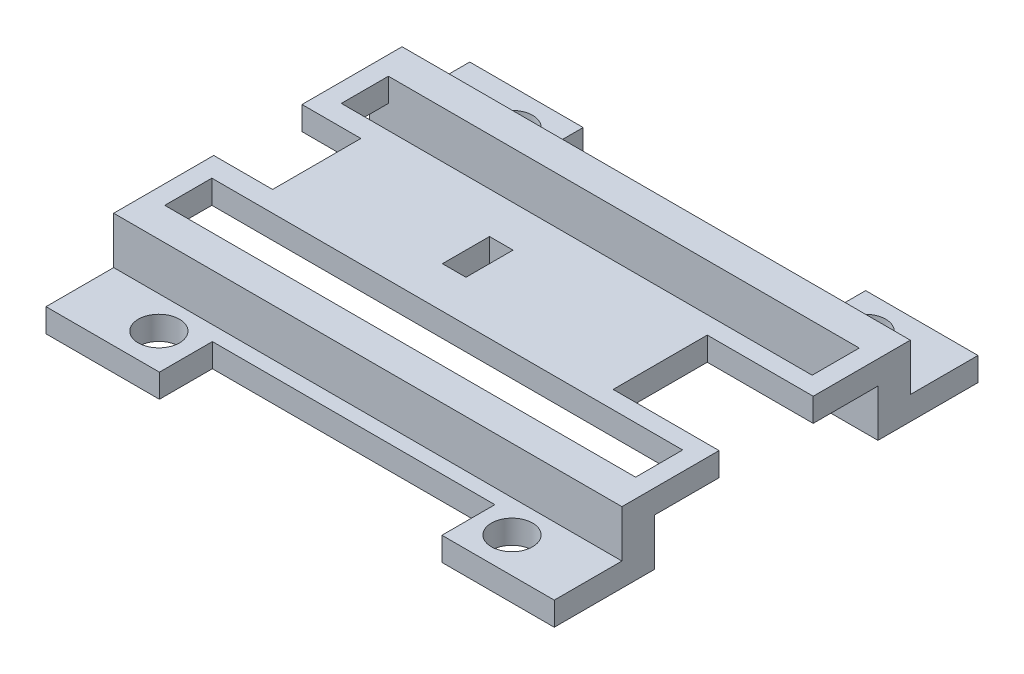
SolidWorks part; units mm, degrees
material "ABS"
ref_plane "Front Plane" through (0, 0, 0) normal (0, 0, 1) x (1, 0, 0)
ref_plane "Top Plane" through (0, 0, 0) normal (0, 1, 0) x (1, 0, 0)
ref_plane "Right Plane" through (0, 0, 0) normal (1, 0, 0) x (0, 0, -1)
sketch "Sketch1" plane through (0, 0, 0) normal (0, 1, 0) x (1, 0, 0)
  line L0 (-34.6173, 0) -> (53.1626, 0) construction
  line L7 (-17.9541, -18) -> (-9.9541, -18)
  line L9 (-17.9541, 18) -> (-9.9541, 18)
  line L20 (19.005, -6.25) -> (19.005, -8.75)
  line L24 (10.0459, 18) -> (10.0459, 12.6161)
  line L26 (19.005, -8.75) -> (18.5047, -8.75)
  line L31 (10.0459, 12.6161) -> (-9.9541, 12.6161)
  line L32 (-9.9541, 18) -> (-9.9541, 12.6161)
  line L33 (-21.59, -18) -> (-9.9541, -18)
  line L34 (-21.59, -18) -> (-21.59, 18)
  line L35 (-21.59, 18) -> (-9.9541, 18)
  line L36 (21.59, -18) -> (21.59, 18)
  line L37 (0, 0) -> (0, 6.25)
  line L38 (18.5047, -6.25) -> (19.005, -6.25)
  line L39 (10.0459, -12.6161) -> (-9.9541, -12.6161)
  line L40 (-9.9541, -18) -> (-9.9541, -12.6161)
  line L42 (10.0459, -18) -> (10.0459, -12.6161)
  line L43 (10.0459, -18) -> (21.59, -18)
  line L44 (10.0459, -18) -> (18.0459, -18)
  line L45 (10.0459, 18) -> (18.0459, 18)
  line L46 (10.0459, 18) -> (21.59, 18)
  line L47 (18.5047, -6.25) -> (-18.5, -6.25)
  line L48 (-19.0045, -6.25) -> (-18.5, -6.25)
  line L49 (-19.0045, -8.75) -> (-19.0045, -6.25)
  line L50 (-18.5, 8.75) -> (18.5047, 8.75)
  line L51 (18.5047, 6.25) -> (-18.5, 6.25)
  line L52 (-18.5, -8.75) -> (-19.0045, -8.75)
  line L53 (0.0024, 8.75) -> (-18.5, 8.75)
  line L54 (0.0024, 8.75) -> (18.5047, 8.75)
  line L55 (-18.5, 8.75) -> (-19.0045, 8.75)
  line L56 (-19.0045, 8.75) -> (-19.0045, 6.25)
  line L57 (-19.0045, 6.25) -> (-18.5, 6.25)
  line L58 (18.5047, 6.25) -> (19.005, 6.25)
  line L59 (19.005, 6.25) -> (19.005, 8.75)
  line L60 (19.005, 8.75) -> (18.5047, 8.75)
  line L61 (-18.5, -8.75) -> (18.5047, -8.75)
  circle A0 centre (-15, 15) radius 1.75
  circle A1 centre (15, 15) radius 1.75
  circle A2 centre (15, -15) radius 1.75
  circle A3 centre (-15, -15) radius 1.75
  point P0 (0, 0)
  point P10 (0, 0)
  point P15 (0, 0)
  point P16 (0, 0)
  point P17 (0.0459, 18)
  point P24 (0, 0)
  dimension "D3" = 3.5
  dimension "D4" = 3.5
  dimension "D5" = 3.5
  dimension "D6" = 3.5
  dimension "D11" = 2.5
  dimension "D12" = 38.0095
  dimension "D13" = 18.5024
  dimension "D14" = 38.0095
  dimension "D1" = 30
  dimension "D2" = 30
  dimension "D7" = 36
  dimension "D8" = 36
  dimension "D9" = 43.18
  dimension "D10" = 20
extrude "Boss-Extrude3" add sketch "Sketch1" along normal blind 3
sketch "Sketch3" plane through (0, 3, 0) normal (0, 1, 0) x (1, 0, 0)
  line L0 (0, 0) -> (-16.59, 0)
  line L1 (-21.59, 9.27) -> (21.59, 9.27)
  line L2 (-21.59, 9.27) -> (-21.59, -9.27)
  line L3 (-21.59, -9.27) -> (21.59, -9.27)
  line L4 (21.59, 9.27) -> (21.59, -9.27)
  line L5 (-21.59, 9.27) -> (21.59, -9.27) construction
  line L6 (-21.59, -9.27) -> (21.59, 9.27) construction
  line L7 (-16.59, 0) -> (36.4752, 0)
  line L8 (21.59, 0) -> (21.59, 3.9995)
  line L9 (21.59, 3.9995) -> (21.59, -3.9981)
  line L10 (21.59, -3.9981) -> (12.59, -3.9981)
  line L11 (12.59, -3.9981) -> (12.59, 3.9995)
  line L12 (12.59, 3.9995) -> (21.59, 3.9995)
  line L13 (-21.59, 0) -> (-21.59, 3.75)
  line L14 (-21.59, 3.75) -> (-21.59, -3.75)
  line L15 (-21.59, -3.75) -> (-16.59, -3.75)
  line L16 (-16.59, -3.75) -> (-16.59, 3.75)
  line L17 (-16.59, 3.75) -> (-21.59, 3.75)
  line L18 (12.59, 0.0007) -> (-3.408, 0)
  line L19 (-16.59, 0) -> (-4.576, 0)
  line L20 (21.59, 0) -> (-1.9118, 0)
  line L21 (-1.9118, 0) -> (-3.9118, 0)
  line L22 (-3.9118, 0) -> (-3.9118, 2)
  line L23 (-3.9118, 2) -> (-1.9118, 2)
  line L24 (-1.9118, 2) -> (-1.9118, -2)
  line L25 (-1.9118, -2) -> (-3.9118, -2)
  line L26 (-3.9118, -2) -> (-3.9118, -0.0848)
  line L27 (-3.9118, -0.0848) -> (-3.9118, 0)
  line L28 (21.59, -18) -> (21.59, 18) construction
  point P0 (0, 0)
  line M24 (-21.59, 18) -> (-21.59, -18)
  dimension "D1" = 43.18
  dimension "D2" = 18.54
  dimension "D3" = 3.75
  dimension "D4" = 3.75
  dimension "D5" = 5
  dimension "D6" = 23.5018
  dimension "D7" = 2
  dimension "D8" = 2
  dimension "D9" = 2
  dimension "D10" = 12.6782
sketch "Sketch4" plane through (0, 3, 0) normal (0, 1, 0) x (1, 0, 0)
  line L0 (-21.59, -9.27) -> (-21.59, -18)
  line L4 (-21.59, -9.27) -> (-21.59, 9.27)
  line L5 (19.005, -8.9) -> (19.255, -8.9)
  line L6 (21.59, 9.27) -> (19.255, 8.2674) construction
  line L7 (-17.4676, -7.5) -> (-22.2811, -7.5) construction
  line L8 (19.255, 6.1) -> (19.255, 8.8828)
  line L9 (-22.2811, -7.5) -> (-22.2811, 7.5) construction
  line L10 (-22.2811, 7.5) -> (-19.2545, 7.5) construction
  line L11 (-21.59, -18) -> (-9.9541, -18)
  line L12 (-9.9541, -18) -> (-9.9541, -12.6161)
  line L13 (-9.9541, -12.6161) -> (10.0459, -12.6161)
  line L14 (10.0459, -12.6161) -> (10.0459, -18)
  line L15 (10.0459, -18) -> (21.59, -18)
  line L18 (-21.59, 9.27) -> (-21.59, 18)
  line L19 (-21.59, 18) -> (-9.9541, 18)
  line L20 (-9.9541, 18) -> (-9.9541, 12.6161)
  line L21 (-9.9541, 12.6161) -> (10.0459, 12.6161)
  line L22 (10.0459, 12.6161) -> (10.0459, 18)
  line L23 (10.0459, 18) -> (21.59, 18)
  line L26 (19.957, 7.5) -> (19.957, -7.5) construction
  line L27 (19.957, -7.5) -> (19.255, -7.5) construction
  line L28 (19.005, 6.1) -> (19.255, 6.1)
  line L29 (19.005, -8.9) -> (-19.0045, -8.9)
  line L30 (-19.2545, -8.2672) -> (-21.59, -9.27) construction
  line L31 (-25.3402, 0) -> (40.0114, 0) construction
  line L32 (19.255, 7.5) -> (19.957, 7.5) construction
  line L33 (19.005, -6.1) -> (-19.0045, -6.1)
  line L35 (-19.0045, -8.9) -> (19.005, -8.9)
  line L37 (-19.0045, -6.1) -> (19.005, -6.1)
  line L39 (-19.0045, 6.1) -> (19.005, 6.1)
  line L41 (-19.0045, 8.9) -> (19.005, 8.9)
  line L43 (19.255, -8.9) -> (19.255, -6.1)
  line L44 (19.255, -6.1) -> (19.005, -6.1)
  line L45 (-19.0045, -6.1) -> (-19.2545, -6.1)
  line L46 (-19.2545, -6.1) -> (-19.2545, -8.9)
  line L47 (-19.2545, -8.9) -> (-19.0045, -8.9)
  line L48 (19.255, 8.9) -> (19.005, 8.9)
  line L49 (-19.0045, 6.1) -> (-19.2545, 6.1)
  line L50 (14.207, 6.1) -> (-17.4676, -7.5) construction
  line L51 (-19.2545, 8.9) -> (-19.0045, 8.9)
  line L52 (-19.2545, 6.1) -> (-19.2545, 8.9)
  line L54 (19.255, -8.9) -> (-19.2545, -8.9)
  line L55 (19.255, -8.9) -> (19.255, -6.1)
  line L56 (19.255, -6.1) -> (-19.2545, -6.1)
  line L57 (-19.2545, -8.9) -> (-19.2545, -6.1)
  line L58 (-19.2545, 6.1) -> (19.255, 6.1)
  line L59 (-19.2545, 6.1) -> (-19.2545, 8.9)
  line L60 (-19.2545, 8.9) -> (19.255, 8.9)
  line L61 (19.255, 6.1) -> (19.255, 8.9)
  circle A1 centre (15, -15) radius 1.75
  circle A2 centre (-15, -15) radius 1.75
  circle A3 centre (-15, 15) radius 1.75
  circle A4 centre (15, 15) radius 1.7781
  point P0 (0, 0)
  line M27 (19.005, -8.75) -> (-19.0045, -8.75)
  line M28 (-19.0045, -8.75) -> (-19.0045, -6.25)
  line M29 (-19.0045, -6.25) -> (19.005, -6.25)
  line M30 (19.005, -6.25) -> (19.005, -8.75)
  line M31 (19.005, 8.75) -> (19.005, 6.25)
  line M32 (19.005, 6.25) -> (-19.0045, 6.25)
  line M33 (-19.0045, 6.25) -> (-19.0045, 8.75)
  line M34 (-19.0045, 8.75) -> (19.005, 8.75)
  dimension "D1" = 18.54
  dimension "D2" = 43.18
  dimension "D3" = 0.25
  dimension "D4" = 0.25
  dimension "D5" = 38.0095
  dimension "D6" = 0.25
  dimension "D7" = 0.25
sketch "Sketch5" plane through (21.59, 0, 0) normal (1, 0, 0) x (0, 0, -1)
  line L0 (0, -5.6906) -> (0, 9.6238) construction
  line L1 (18, -1) -> (11.53, -1)
  line L2 (-18, 3) -> (-11.53, 3)
  line L3 (-18, 3) -> (-18, -1)
  line L4 (-18, -1) -> (-11.53, -1)
  line L5 (-11.53, 3) -> (-11.53, -1)
  line L6 (11.53, 3) -> (11.53, -1)
  line L7 (18, 3) -> (11.53, 3)
  line L8 (18, 3) -> (18, -1)
  dimension "D1" = 4
  dimension "D2" = 6.47
extrude "Cut-Extrude7" cut sketch "Sketch4" against normal through all contours M31 M34 M33 M32 | L8 L61 L48 L41 L51 L52 L49 L39 L28 M34 M31 M32 M33 | L46 L47 L29 L5 L43 L44 L33 L45 M30 M27 M28 M29
sketch "Sketch7" plane through (21.59, 0, 0) normal (1, 0, 0) x (0, 0, -1)
  line L0 (-18, 0) -> (-18, 1)
  line L5 (-18, 3) -> (-18, -1) construction
  line L7 (18, 0) -> (-18, 0)
  line L8 (18, 0) -> (18, 1)
  line L9 (18, 1) -> (-18, 1)
  line L10 (-18, 0) -> (-18, 1)
  line M6 (-18, 0) -> (18, 0)
  line M7 (18, 0) -> (18, 3)
  line M9 (-18, 3) -> (-18, 0)
  dimension "D1" = 1
extrude "Cut-Extrude8" cut sketch "Sketch7" against normal through all contours L9 M7 M9 M6
sketch "Sketch9" plane through (0, 3, 0) normal (0, 1, 0) x (1, 0, 0)
  line L0 (-26.5021, 0) -> (31.2458, 0) construction
  line L3 (-19.2545, -6.1) -> (-19.2545, -8.9)
  line L4 (-19.2545, -8.9) -> (19.255, -8.9)
  line L5 (19.255, -8.9) -> (19.255, -6.1)
  line L6 (19.255, -6.1) -> (-19.2545, -6.1)
  line L7 (19.255, -8.9) -> (-19.2545, -6.1)
  line L8 (-19.2545, -8.9) -> (19.255, -6.1)
  line L10 (-18.9908, -9.45) -> (18.9912, -9.45)
  line L11 (-18.9908, -9.45) -> (-18.9908, -5.55)
  line L12 (-18.9908, -5.55) -> (18.9912, -5.55)
  line L13 (18.9912, -9.45) -> (18.9912, -5.55)
  line L14 (-18.9908, -9.45) -> (18.9912, -5.55) construction
  line L15 (-18.9908, -5.55) -> (18.9912, -9.45) construction
  line L19 (19.9912, 5.5492) -> (19.9912, 9.4508)
  line L20 (-19.9908, -5.5492) -> (19.9912, -5.5492)
  line L21 (-19.9908, -5.5492) -> (-19.9908, -9.4508)
  line L22 (-19.9908, -9.4508) -> (19.9912, -9.4508)
  line L23 (19.9912, -5.5492) -> (19.9912, -9.4508)
  line L24 (-19.9908, -5.5492) -> (19.9912, -9.4508) construction
  line L25 (-19.9908, -9.4508) -> (19.9912, -5.5492) construction
  line L26 (-19.9908, -9.4508) -> (19.9912, -9.4508)
  line L27 (-19.9908, -9.4508) -> (-19.9908, -5.5492)
  line L28 (-19.9908, -5.5492) -> (19.9912, -5.5492)
  line L29 (19.9912, -9.4508) -> (19.9912, -5.5492)
  line L30 (-19.9908, 5.5492) -> (19.9912, 5.5492)
  line L31 (-19.9908, 9.4508) -> (19.9912, 9.4508)
  line L32 (-19.9908, 5.5492) -> (-19.9908, 9.4508)
  point P5 (0.0002, -7.5)
  point P20 (0.0002, -7.5)
  line M9 (19.255, 8.9) -> (19.255, 6.1)
  line M10 (19.255, 6.1) -> (-19.2545, 6.1)
  line M11 (-19.2545, 6.1) -> (-19.2545, 8.9)
  line M12 (-19.2545, 8.9) -> (19.255, 8.9)
  line M13 (-19.2545, -8.9) -> (-19.2545, -6.1)
  line M14 (-19.2545, -6.1) -> (19.255, -6.1)
  line M15 (19.255, -6.1) -> (19.255, -8.9)
  line M16 (19.255, -8.9) -> (-19.2545, -8.9)
  dimension "D1" = 3.9
  dimension "D2" = 1
  dimension "D3" = 1
extrude "Cut-Extrude9" cut sketch "Sketch9" against normal blind 10 contours L10 L13 L4 L11 | L32 L30 L19 L31 M12 M9 M10 M11 | L6 L13 L12 L11 | L23 L20 L21 L22 L13 L10 L11 L4 L12 M13 M14 M15 M16
sketch "Sketch10" plane through (0, 3, 0) normal (0, 1, 0) x (1, 0, 0)
  line L1 (-19.9908, -5.5492) -> (-19.9908, -9.4508)
  line L3 (19.9912, -5.5492) -> (19.9912, -9.4508)
  line L4 (0, 0) -> (29.449, 0) construction
  line L5 (-19.9998, -5.5) -> (20.0002, -5.5)
  line L6 (-19.9998, -5.5) -> (-19.9998, -9.5)
  line L7 (-19.9998, -9.5) -> (20.0002, -9.5)
  line L8 (20.0002, -5.5) -> (20.0002, -9.5)
  line L9 (-19.9998, -5.5) -> (20.0002, -9.5) construction
  line L10 (-19.9998, -9.5) -> (20.0002, -5.5) construction
  line L11 (29.449, 0) -> (-32.5926, 0) construction
  line L13 (-19.9908, 9.4508) -> (-19.9908, 5.5492)
  line L16 (-19.9998, 5.5) -> (20.0002, 5.5)
  line L17 (-19.9998, 5.5) -> (-19.9998, 9.5)
  line L18 (-19.9998, 9.5) -> (20.0002, 9.5)
  line L19 (20.0002, 5.5) -> (20.0002, 9.5)
  line L20 (-19.9998, 5.5) -> (20.0002, 9.5) construction
  line L21 (-19.9998, 9.5) -> (20.0002, 5.5) construction
  point P4 (0.0002, -7.5)
  point P20 (0.0002, 7.5)
  line M7 (-19.9908, -5.5492) -> (19.9912, -5.5492)
  line M8 (19.9912, -5.5492) -> (19.9912, -9.4508)
  line M9 (19.9912, -9.4508) -> (-19.9908, -9.4508)
  line M10 (-19.9908, -9.4508) -> (-19.9908, -5.5492)
  line M27 (19.9912, 5.5492) -> (-19.9908, 5.5492)
  line M28 (-19.9908, 5.5492) -> (-19.9908, 9.4508)
  line M29 (-19.9908, 9.4508) -> (19.9912, 9.4508)
  line M30 (19.9912, 9.4508) -> (19.9912, 5.5492)
  dimension "D1" = 4
  dimension "D2" = 40
  dimension "D3" = 4
  dimension "D4" = 40
extrude "Cut-Extrude11" cut sketch "Sketch10" against normal through all contours M27 M30 M29 M28 | L8 L5 L6 L7 M10 M7 M8 M9 | L16 L19 L18 L17 M30 M27 M28 M29
sketch "Sketch11" plane through (0, 3, 0) normal (0, 1, 0) x (1, 0, 0)
  line L0 (-9.9541, 18) -> (-9.9541, 12.6161) construction
  line L1 (10.0459, -12.6161) -> (-9.9541, -12.6161)
  line L2 (10.0459, -12.6161) -> (10.0459, 12.6161)
  line L3 (10.0459, 12.6161) -> (-9.9541, 12.6161)
  line L4 (-9.9541, -12.6161) -> (-9.9541, 12.6161)
  line L5 (10.0459, 12.6161) -> (-9.9541, 12.6161) construction
  line L6 (10.0459, -9.5) -> (-9.9541, -9.5)
  line L7 (-19.9998, -9.5) -> (20.0002, -9.5) construction
  line L8 (-9.9541, 9.4749) -> (10.0459, 9.5)
  line L9 (-19.9998, 9.5) -> (20.0002, 9.5) construction
  line M12 (10.0459, 12.6161) -> (-9.9541, 12.6161)
  line M18 (-9.9541, -12.6161) -> (10.0459, -12.6161)
  line M23 (-19.9998, 9.5) -> (20.0002, 9.5)
  line M27 (20.0002, -9.5) -> (-19.9998, -9.5)
extrude "Cut-Extrude12" cut sketch "Sketch11" against normal blind 10 contours L4 L2 M18 M27 | L4 L2 M23 M12
sketch "Sketch12" plane through (0, 3, 0) normal (0, 1, 0) x (1, 0, 0)
  line L0 (-9.9541, -18) -> (-11.9541, -18)
  line L1 (-21.59, -18) -> (-9.9541, -18) construction
  line L2 (-11.9541, -18) -> (-11.9541, 18)
  line L3 (-21.59, 18) -> (-9.9541, 18) construction
  line L4 (-11.9541, 18) -> (-9.9541, 18)
  line L5 (-9.9541, 18) -> (-9.9541, -18)
  line L6 (10.0459, -18) -> (12.0459, -18)
  line L7 (10.0459, -18) -> (21.59, -18) construction
  line L8 (12.0459, -18) -> (12.0459, 18)
  line L9 (10.0459, 18) -> (21.59, 18) construction
  line L10 (12.0459, 18) -> (10.0459, 18)
  line L11 (10.0459, 18) -> (10.0459, -18)
  line L12 (10.0459, 9.5) -> (20.0002, 9.5) construction
  line L13 (-11.9541, -18) -> (-9.9541, -18)
  line L14 (-11.9541, -18) -> (-11.9541, -9.5)
  line L15 (-11.9541, -9.5) -> (-9.9541, -9.5)
  line L16 (-9.9541, -18) -> (-9.9541, -9.5)
  line L17 (10.0459, -18) -> (12.0459, -18)
  line L18 (10.0459, -18) -> (10.0459, -9.6559)
  line L20 (12.0459, -18) -> (12.0459, -9.6559)
  line L21 (10.0459, 18) -> (12.0459, 18)
  line L22 (10.0459, 18) -> (10.0459, 9.5)
  line L23 (10.0459, 9.5) -> (12.0459, 9.5)
  line L24 (12.0459, 18) -> (12.0459, 9.5)
  line L26 (-11.9541, 18) -> (-9.9541, 18)
  line L27 (-11.9541, 18) -> (-11.9541, 9.5)
  line L28 (-11.9541, 9.5) -> (-9.9541, 9.5)
  line L29 (-9.9541, 18) -> (-9.9541, 9.5)
  line L30 (10.0459, -9.5) -> (12.0459, -9.5)
  line L31 (10.0459, -9.5) -> (10.0459, -18)
  line L32 (10.0459, -18) -> (12.0459, -18)
  line L33 (12.0459, -9.5) -> (12.0459, -18)
  line M10 (-9.9541, -18) -> (-9.9541, -9.5)
  line M11 (-9.9541, -9.5) -> (-19.9998, -9.5)
  line M15 (20.0002, -9.5) -> (10.0459, -9.5)
  line M16 (10.0459, -9.5) -> (10.0459, -18)
  line M17 (10.0459, -18) -> (21.59, -18)
  line M19 (21.59, 18) -> (10.0459, 18)
  line M20 (10.0459, 18) -> (10.0459, 9.5)
  line M21 (10.0459, 9.5) -> (20.0002, 9.5)
  line M25 (-19.9998, 9.5) -> (-9.9541, 9.5)
  line M26 (-9.9541, 9.5) -> (-9.9541, 18)
  line M27 (-9.9541, 18) -> (-21.59, 18)
  line M29 (-21.59, -18) -> (-9.9541, -18)
  dimension "D1" = 2
  dimension "D2" = 2
extrude "Cut-Extrude15" cut sketch "Sketch12" against normal blind 10 contours L2 M29 M10 M11 | L2 M25 M26 M27 | L8 M21 M19 M20 | L8 L11 M17 M15 M16
sketch "Croquis1" plane through (0, 3, 0) normal (0, 1, 0) x (1, 0, 0)
  line L0 (-11.9541, -13.5) -> (12.0459, -13.5)
  line L1 (-11.9541, 13.5) -> (12.0459, 13.5)
  line L2 (-11.9541, -9.5) -> (12.0459, -9.5)
  line L3 (-11.9541, 9.5) -> (12.0459, 9.5)
  line L20 (12.0459, -9.5) -> (12.0459, -18)
  line L21 (12.0459, -18) -> (21.59, -18)
  line L22 (21.59, -18) -> (21.59, 18)
  line L23 (21.59, 18) -> (12.0459, 18)
  line L24 (12.0459, 18) -> (12.0459, 9.5)
  line L25 (12.0459, 9.5) -> (20.0002, 9.5)
  line L26 (20.0002, 9.5) -> (20.0002, 5.5)
  line L27 (20.0002, 5.5) -> (-19.9998, 5.5)
  line L28 (-19.9998, 5.5) -> (-19.9998, 9.5)
  line L29 (-19.9998, 9.5) -> (-11.9541, 9.5)
  line L30 (-11.9541, 9.5) -> (-11.9541, 18)
  line L31 (-11.9541, 18) -> (-21.59, 18)
  line L32 (-21.59, 18) -> (-21.59, -18)
  line L33 (-21.59, -18) -> (-11.9541, -18)
  line L34 (-11.9541, -18) -> (-11.9541, -9.5)
  line L35 (-11.9541, -9.5) -> (-19.9998, -9.5)
  line L36 (-19.9998, -9.5) -> (-19.9998, -5.5)
  line L37 (-19.9998, -5.5) -> (20.0002, -5.5)
  line L38 (20.0002, -5.5) -> (20.0002, -9.5)
  line L39 (20.0002, -9.5) -> (12.0459, -9.5)
  line L40 (12.0459, -9.5) -> (12.0459, -13.5)
  line L44 (12.0459, 13.5) -> (12.0459, 9.5)
  line L50 (-11.9541, 9.5) -> (-11.9541, 13.5)
  line L54 (-11.9541, -13.5) -> (-11.9541, -9.5)
  dimension "D2" = 4
  dimension "D3" = 4
  dimension "D1" = 0
extrude "Saliente-Extruir1" add sketch "Croquis1" against normal up to surface (2 mm away) up to face at (15, 1, -13.25)
sketch "Croquis2" plane through (0, 3, 0) normal (0, 1, 0) x (1, 0, 0)
  line L4 (-19.9998, 5.5) -> (-19.9998, 9.5) construction
  line L5 (-19.9998, 9.5) -> (20.0002, 9.5) construction
  line L6 (-19.9998, 5.5) -> (20.0002, 5.5) construction
  line L7 (20.0002, 5.5) -> (20.0002, 9.5) construction
  line L8 (20.0002, -5.5) -> (20.0002, -9.5) construction
  line L9 (-19.9998, -9.5) -> (20.0002, -9.5) construction
  line L10 (-19.9998, -5.5) -> (-19.9998, -9.5) construction
  line L11 (-19.9998, -5.5) -> (20.0002, -5.5) construction
  line L12 (-19.9998, 5.5) -> (-19.9998, 9.5)
  line L13 (-19.9998, 9.5) -> (20.0002, 9.5)
  line L14 (-19.9998, 5.5) -> (20.0002, 5.5)
  line L15 (20.0002, 5.5) -> (20.0002, 9.5)
  line L16 (12.0459, 18) -> (12.0459, 13.5)
  line L17 (12.0459, 13.5) -> (-11.9541, 13.5)
  line L18 (-11.9541, 13.5) -> (-11.9541, 18)
  line L19 (-11.9541, 18) -> (-21.59, 18)
  line L20 (-21.59, 18) -> (-21.59, -18)
  line L21 (-21.59, -18) -> (-11.9541, -18)
  line L22 (-11.9541, -18) -> (-11.9541, -13.5)
  line L23 (-11.9541, -13.5) -> (12.0459, -13.5)
  line L24 (12.0459, -13.5) -> (12.0459, -18)
  line L25 (12.0459, -18) -> (21.59, -18)
  line L26 (21.59, -18) -> (21.59, 18)
  line L27 (21.59, 18) -> (12.0459, 18)
  line L32 (-21.59, 12.25) -> (-21.59, -12.25)
  line L38 (21.59, -12.25) -> (21.59, 12.25)
  line L40 (20.0002, -5.5) -> (20.0002, -9.5)
  line L41 (-19.9998, -9.5) -> (20.0002, -9.5)
  line L42 (-19.9998, -5.5) -> (-19.9998, -9.5)
  line L43 (-19.9998, -5.5) -> (20.0002, -5.5)
  line L44 (-21.59, -12.25) -> (21.59, -12.25)
  line L45 (-21.59, 12.25) -> (21.59, 12.25)
  line L46 (-21.59, -9.27) -> (-21.59, 9.27)
  line L47 (21.59, -9.27) -> (21.59, 9.27)
  line M21 (-21.59, 18) -> (-21.59, -18)
  line M27 (21.59, -18) -> (21.59, 18)
  line M29 (20.0002, -5.5) -> (20.0002, -9.5)
  line M30 (20.0002, -9.5) -> (-19.9998, -9.5)
  line M31 (-19.9998, -9.5) -> (-19.9998, -5.5)
  line M32 (-19.9998, -5.5) -> (20.0002, -5.5)
  line M33 (-19.9998, 9.5) -> (20.0002, 9.5)
  line M34 (20.0002, 9.5) -> (20.0002, 5.5)
  line M35 (20.0002, 5.5) -> (-19.9998, 5.5)
  line M36 (-19.9998, 5.5) -> (-19.9998, 9.5)
  dimension "D2" = 2.75
  dimension "D3" = 2.75
  dimension "D1" = 0
extrude "Saliente-Extruir2" add sketch "Croquis2" along normal blind 4 contours L45 L32 L44 L38 M21 M27 M36 M33 M34 M35 M32 M29 M30 M31
sketch "Croquis4" plane through (0, 1, 0) normal (0, -1, 0) x (1, 0, 0)
  line L4 (-21.59, -18) -> (-21.59, 18) construction
  line L5 (-21.59, -9.5) -> (-21.59, 9.5)
  line L6 (20.0002, 5.5) -> (20.0002, 9.5) construction
  line L7 (-19.9998, 5.5) -> (20.0002, 5.5) construction
  line L8 (-19.9998, -5.5) -> (20.0002, -5.5) construction
  line L9 (20.0002, -5.5) -> (20.0002, -9.5) construction
  line L10 (20.0002, 5.5) -> (20.0002, 9.5)
  line L11 (-19.9998, 5.5) -> (20.0002, 5.5)
  line L12 (-11.9541, -13.5) -> (12.0459, -13.5)
  line L13 (12.0459, -13.5) -> (12.0459, -18)
  line L14 (12.0459, -18) -> (21.59, -18)
  line L15 (21.59, -18) -> (21.59, 18)
  line L16 (21.59, 18) -> (12.0459, 18)
  line L17 (12.0459, 18) -> (12.0459, 13.5)
  line L18 (12.0459, 13.5) -> (-11.9541, 13.5)
  line L19 (-11.9541, 13.5) -> (-11.9541, 18)
  line L20 (-11.9541, 18) -> (-21.59, 18)
  line L21 (-21.59, 18) -> (-21.59, -18)
  line L22 (-21.59, -18) -> (-11.9541, -18)
  line L23 (-11.9541, -18) -> (-11.9541, -13.5)
  line L27 (21.59, -9.5) -> (21.59, 9.5)
  line L36 (-19.9998, -5.5) -> (20.0002, -5.5)
  line L37 (20.0002, -5.5) -> (20.0002, -9.5)
  line L38 (-19.9998, 5.5) -> (-19.9998, 9.5) construction
  line L39 (-19.9998, -5.5) -> (-19.9998, -9.5) construction
  line L40 (-19.9998, 5.5) -> (-19.9998, 9.5)
  line L41 (-19.9998, -5.5) -> (-19.9998, -9.5)
  line L42 (-21.59, -9.5) -> (-19.9998, -9.5)
  line L43 (-21.59, 9.5) -> (-19.9998, 9.5)
  line L44 (21.59, -9.5) -> (20.0002, -9.5)
  line L45 (21.59, 9.5) -> (20.0002, 9.5)
  dimension "D1" = 0
extrude "Cortar-Extruir2" cut sketch "Croquis4" against normal blind 4
extrude "Cortar-Extruir5" cut sketch "Sketch3" along normal blind 4 contours L27 L26 L25 L24 L7 | L24 L23 L22 L7 L18 | L12 L11 L7 L4 | L11 L10 L4 L7 | L16 L17 L2 L15 M24
